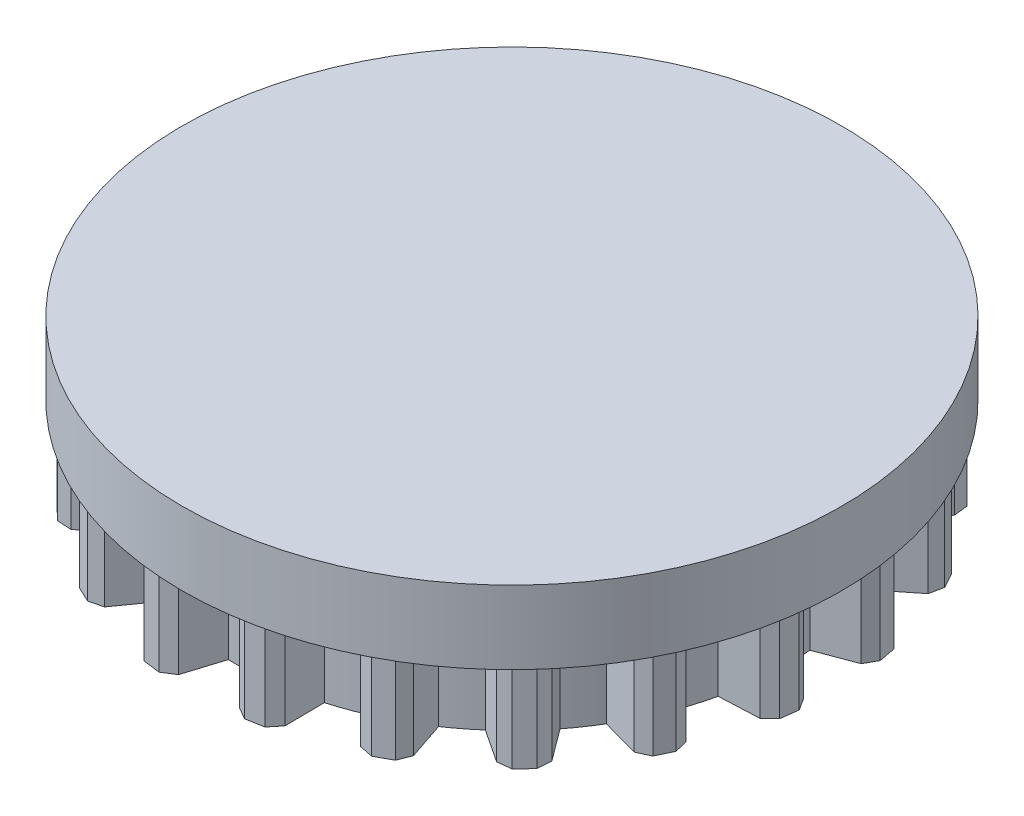
SolidWorks part; units mm, degrees
ref_plane "Front Plane" through (0, 0, 0) normal (0, 0, 1) x (1, 0, 0)
ref_plane "Top Plane" through (0, 0, 0) normal (0, 1, 0) x (1, 0, 0)
ref_plane "Right Plane" through (0, 0, 0) normal (1, 0, 0) x (0, 0, -1)
sketch "Sketch1" plane through (0, 0, 0) normal (0, 1, 0) x (1, 0, 0)
  line L0 (-358.2859, 129.5847) -> (-403.3024, 161.58)
  line L1 (-403.3024, 161.58) -> (-408.206, 180.4095)
  line L2 (-408.206, 180.4095) -> (-397.7834, 202.3565)
  line L3 (-397.7834, 202.3565) -> (-380.0914, 210.4553)
  line L4 (-380.0914, 210.4553) -> (-326.8467, 195.7861)
  line L5 (-300.7063, 233.9588) -> (-333.6324, 278.299)
  line L6 (-333.6324, 278.299) -> (-332.4774, 297.7222)
  line L7 (-332.4774, 297.7222) -> (-315.7829, 315.3743)
  line L8 (-315.7829, 315.3743) -> (-296.4542, 317.6096)
  line L9 (-296.4542, 317.6096) -> (-250.3485, 287.2049)
  line L10 (-213.6914, 315.4314) -> (-231.3042, 367.7762)
  line L11 (-231.3042, 367.7762) -> (-224.2036, 385.8918)
  line L12 (-224.2036, 385.8918) -> (-202.8714, 397.521)
  line L13 (-202.8714, 397.521) -> (-183.7979, 393.6741)
  line L14 (-183.7979, 393.6741) -> (-149.3444, 350.51)
  line L15 (-105.7589, 366.0274) -> (-106.3343, 421.2528)
  line L16 (-106.3343, 421.2528) -> (-93.9831, 436.2877)
  line L17 (-93.9831, 436.2877) -> (-70.1014, 440.7557)
  line L18 (-70.1014, 440.7557) -> (-53.1502, 431.203)
  line L19 (-53.1502, 431.203) -> (-33.7214, 379.5048)
  line L20 (12.526, 380.794) -> (29.0444, 433.4944)
  line L21 (29.0444, 433.4944) -> (45.437, 443.9766)
  line L22 (45.437, 443.9766) -> (69.5306, 440.8461)
  line L23 (69.5306, 440.8461) -> (82.7002, 426.5227)
  line L24 (82.7002, 426.5227) -> (85.2025, 371.351)
  line L25 (129.5847, 358.2859) -> (161.58, 403.3024)
  line L26 (161.58, 403.3024) -> (180.4095, 408.206)
  line L27 (180.4095, 408.206) -> (202.3565, 397.7834)
  line L28 (202.3565, 397.7834) -> (210.4553, 380.0914)
  line L29 (210.4553, 380.0914) -> (195.7861, 326.8467)
  line L30 (233.9588, 300.7063) -> (278.299, 333.6324)
  line L31 (278.299, 333.6324) -> (297.7222, 332.4774)
  line L32 (297.7222, 332.4774) -> (315.3743, 315.7829)
  line L33 (315.3743, 315.7829) -> (317.6096, 296.4542)
  line L34 (317.6096, 296.4542) -> (287.2049, 250.3485)
  line L35 (315.4314, 213.6914) -> (367.7762, 231.3042)
  line L36 (367.7762, 231.3042) -> (385.8918, 224.2036)
  line L37 (385.8918, 224.2036) -> (397.521, 202.8714)
  line L38 (397.521, 202.8714) -> (393.6741, 183.7979)
  line L39 (393.6741, 183.7979) -> (350.51, 149.3444)
  line L40 (366.0274, 105.7589) -> (421.2528, 106.3343)
  line L41 (421.2528, 106.3343) -> (436.2877, 93.9831)
  line L42 (436.2877, 93.9831) -> (440.7557, 70.1014)
  line L43 (440.7557, 70.1014) -> (431.203, 53.1502)
  line L44 (431.203, 53.1502) -> (379.5048, 33.7214)
  line L45 (380.794, -12.526) -> (433.4944, -29.0444)
  line L46 (433.4944, -29.0444) -> (443.9766, -45.437)
  line L47 (443.9766, -45.437) -> (440.8461, -69.5306)
  line L48 (440.8461, -69.5306) -> (426.5227, -82.7002)
  line L49 (426.5227, -82.7002) -> (371.351, -85.2025)
  line L50 (358.2859, -129.5847) -> (403.3024, -161.58)
  line L51 (403.3024, -161.58) -> (408.206, -180.4095)
  line L52 (408.206, -180.4095) -> (397.7834, -202.3565)
  line L53 (397.7834, -202.3565) -> (380.0914, -210.4553)
  line L54 (380.0914, -210.4553) -> (326.8467, -195.7861)
  line L55 (300.7063, -233.9588) -> (333.6324, -278.299)
  line L56 (333.6324, -278.299) -> (332.4774, -297.7222)
  line L57 (332.4774, -297.7222) -> (315.7829, -315.3743)
  line L58 (315.7829, -315.3743) -> (296.4542, -317.6096)
  line L59 (296.4542, -317.6096) -> (250.3485, -287.2049)
  line L60 (213.6914, -315.4314) -> (231.3042, -367.7762)
  line L61 (231.3042, -367.7762) -> (224.2036, -385.8918)
  line L62 (224.2036, -385.8918) -> (202.8714, -397.521)
  line L63 (202.8714, -397.521) -> (183.7979, -393.6741)
  line L64 (183.7979, -393.6741) -> (149.3444, -350.51)
  line L65 (105.7589, -366.0274) -> (106.3343, -421.2528)
  line L66 (106.3343, -421.2528) -> (93.9831, -436.2877)
  line L67 (93.9831, -436.2877) -> (70.1014, -440.7557)
  line L68 (70.1014, -440.7557) -> (53.1502, -431.203)
  line L69 (53.1502, -431.203) -> (33.7214, -379.5048)
  line L70 (-12.526, -380.794) -> (-29.0444, -433.4944)
  line L71 (-29.0444, -433.4944) -> (-45.437, -443.9766)
  line L72 (-45.437, -443.9766) -> (-69.5306, -440.8461)
  line L73 (-69.5306, -440.8461) -> (-82.7002, -426.5227)
  line L74 (-82.7002, -426.5227) -> (-85.2025, -371.351)
  line L75 (-129.5847, -358.2859) -> (-161.58, -403.3024)
  line L76 (-161.58, -403.3024) -> (-180.4095, -408.206)
  line L77 (-180.4095, -408.206) -> (-202.3565, -397.7834)
  line L78 (-202.3565, -397.7834) -> (-210.4553, -380.0914)
  line L79 (-210.4553, -380.0914) -> (-195.7861, -326.8467)
  line L80 (-233.9588, -300.7063) -> (-278.299, -333.6324)
  line L81 (-278.299, -333.6324) -> (-297.7222, -332.4774)
  line L82 (-297.7222, -332.4774) -> (-315.3743, -315.7829)
  line L83 (-315.3743, -315.7829) -> (-317.6096, -296.4542)
  line L84 (-317.6096, -296.4542) -> (-287.2049, -250.3485)
  line L85 (-315.4314, -213.6914) -> (-367.7762, -231.3042)
  line L86 (-367.7762, -231.3042) -> (-385.8918, -224.2036)
  line L87 (-385.8918, -224.2036) -> (-397.521, -202.8714)
  line L88 (-397.521, -202.8714) -> (-393.6741, -183.7979)
  line L89 (-393.6741, -183.7979) -> (-350.51, -149.3444)
  line L90 (-366.0274, -105.7589) -> (-421.2528, -106.3343)
  line L91 (-421.2528, -106.3343) -> (-436.2877, -93.9831)
  line L92 (-436.2877, -93.9831) -> (-440.7557, -70.1014)
  line L93 (-440.7557, -70.1014) -> (-431.203, -53.1502)
  line L94 (-431.203, -53.1502) -> (-379.5048, -33.7214)
  line L95 (-380.794, 12.526) -> (-433.4944, 29.0444)
  line L96 (-433.4944, 29.0444) -> (-443.9766, 45.437)
  line L97 (-443.9766, 45.437) -> (-440.8461, 69.5306)
  line L98 (-440.8461, 69.5306) -> (-426.5227, 82.7002)
  line L99 (-426.5227, 82.7002) -> (-371.351, 85.2025)
  arc A0 (-300.7063, 233.9588) -> (-326.8467, 195.7861) centre (0, 0) ccw
  arc A1 (-213.6914, 315.4314) -> (-250.3485, 287.2049) centre (0, 0) ccw
  arc A2 (-105.7589, 366.0274) -> (-149.3444, 350.51) centre (0, 0) ccw
  arc A3 (12.526, 380.794) -> (-33.7214, 379.5048) centre (0, 0) ccw
  arc A4 (129.5847, 358.2859) -> (85.2025, 371.351) centre (0, 0) ccw
  arc A5 (233.9588, 300.7063) -> (195.7861, 326.8467) centre (0, 0) ccw
  arc A6 (315.4314, 213.6914) -> (287.2049, 250.3485) centre (0, 0) ccw
  arc A7 (366.0274, 105.7589) -> (350.51, 149.3444) centre (0, 0) ccw
  arc A8 (380.794, -12.526) -> (379.5048, 33.7214) centre (0, 0) ccw
  arc A9 (358.2859, -129.5847) -> (371.351, -85.2025) centre (0, 0) ccw
  arc A10 (300.7063, -233.9588) -> (326.8467, -195.7861) centre (0, 0) ccw
  arc A11 (213.6914, -315.4314) -> (250.3485, -287.2049) centre (0, 0) ccw
  arc A12 (105.7589, -366.0274) -> (149.3444, -350.51) centre (0, 0) ccw
  arc A13 (-12.526, -380.794) -> (33.7214, -379.5048) centre (0, 0) ccw
  arc A14 (-129.5847, -358.2859) -> (-85.2025, -371.351) centre (0, 0) ccw
  arc A15 (-233.9588, -300.7063) -> (-195.7861, -326.8467) centre (0, 0) ccw
  arc A16 (-315.4314, -213.6914) -> (-287.2049, -250.3485) centre (0, 0) ccw
  arc A17 (-366.0274, -105.7589) -> (-350.51, -149.3444) centre (0, 0) ccw
  arc A18 (-380.794, 12.526) -> (-379.5048, -33.7214) centre (0, 0) ccw
  arc A19 (-358.2859, 129.5847) -> (-371.351, 85.2025) centre (0, 0) ccw
extrude "Boss-Extrude2" add sketch "Sketch1" along normal blind 127
sketch "Sketch3" plane through (0, 127, 0) normal (0, 1, 0) x (1, 0, 0)
  circle A0 centre (0, 0) radius 457.2
  dimension "D1" = 914.4
extrude "Boss-Extrude3" add sketch "Sketch3" along normal blind 101.6
sketch "Sketch4" plane through (0, 0, 0) normal (0, -1, 0) x (-1, 0, 0)
  circle A0 centre (0, 0) radius 63.5
  dimension "D1" = 127
extrude "Cut-Extrude1" cut sketch "Sketch4" against normal blind 76.2
